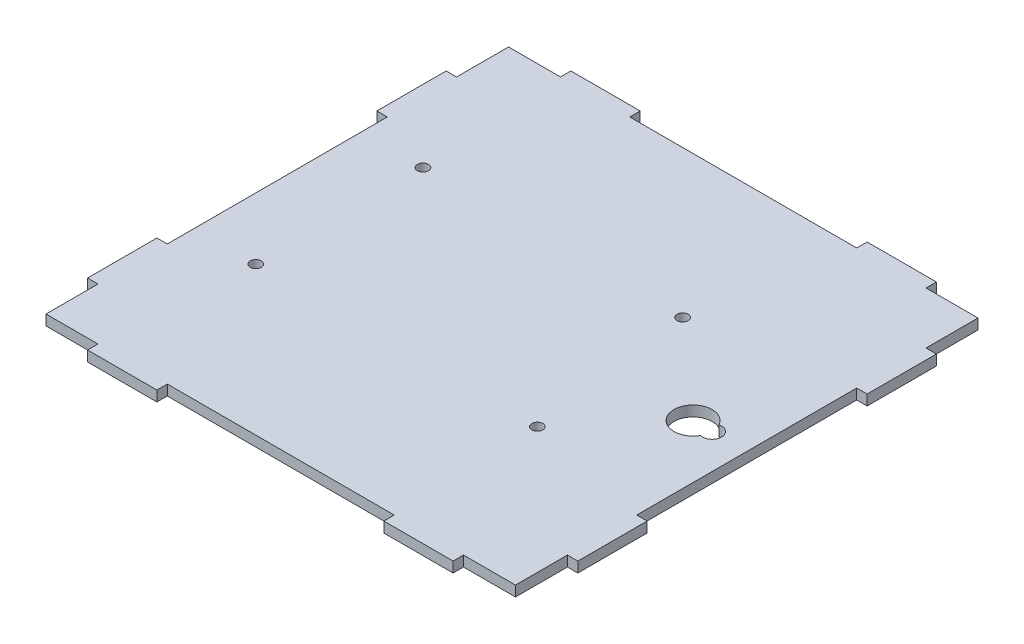
SolidWorks part; units mm, degrees
ref_plane "Спереди" through (0, 0, 0) normal (0, 0, 1) x (1, 0, 0)
ref_plane "Сверху" through (0, 0, 0) normal (0, 1, 0) x (1, 0, 0)
ref_plane "Справа" through (0, 0, 0) normal (1, 0, 0) x (0, 0, -1)
sketch "Sketch1" plane through (0, 0, 0) normal (0, 1, 0) x (1, 0, 0)
  line L0 (-47.661, 21.5312) -> (54.039, 21.5312) construction
  line L1 (-51.461, 61.5312) -> (84.039, 61.5312)
  line L2 (-51.461, 61.5312) -> (-51.461, -71.9688)
  line L3 (-51.461, -71.9688) -> (84.039, -71.9688)
  line L4 (84.039, 61.5312) -> (84.039, -71.9688)
  line L5 (54.039, -31.9688) -> (-47.661, -31.9688) construction
  line L6 (54.039, 21.5312) -> (54.039, -31.9688) construction
  point P0 (0, 0)
  point P8 (52.8389, -53.9712)
  point P9 (70.544, -51.7921)
  dimension "D1" = 40
  dimension "D2" = 40
  dimension "D3" = 30
extrude "Boss-Extrude1" add sketch "Sketch1" along normal blind 3
sketch "Sketch2" plane through (0, 3, 0) normal (0, 1, 0) x (1, 0, 0)
  line L0 (84.039, -71.9688) -> (84.039, 61.5312) construction
  line L1 (84.039, 46.5312) -> (87.039, 46.5312)
  line L2 (84.039, 46.5312) -> (84.039, 26.5312)
  line L3 (84.039, 26.5312) -> (87.039, 26.5312)
  line L4 (87.039, 46.5312) -> (87.039, 26.5312)
  line L5 (84.039, 61.5312) -> (-51.461, 61.5312) construction
  line L6 (84.039, -36.9688) -> (87.039, -36.9688)
  line L7 (84.039, -36.9688) -> (84.039, -56.9688)
  line L8 (84.039, -56.9688) -> (87.039, -56.9688)
  line L9 (87.039, -36.9688) -> (87.039, -56.9688)
  line L10 (69.039, 61.5312) -> (49.039, 61.5312)
  line L11 (69.039, 61.5312) -> (69.039, 64.5312)
  line L12 (69.039, 64.5312) -> (49.039, 64.5312)
  line L13 (49.039, 61.5312) -> (49.039, 64.5312)
  line L14 (-51.461, 61.5312) -> (-51.461, -71.9688) construction
  line L15 (-16.461, 61.5312) -> (-36.461, 61.5312)
  line L16 (-16.461, 61.5312) -> (-16.461, 64.5312)
  line L17 (-16.461, 64.5312) -> (-36.461, 64.5312)
  line L18 (-36.461, 61.5312) -> (-36.461, 64.5312)
  line L19 (-51.461, 46.5312) -> (-54.461, 46.5312)
  line L20 (-51.461, 46.5312) -> (-51.461, 26.5312)
  line L21 (-51.461, 26.5312) -> (-54.461, 26.5312)
  line L22 (-54.461, 46.5312) -> (-54.461, 26.5312)
  line L23 (-51.461, -71.9688) -> (84.039, -71.9688) construction
  line L24 (-51.461, -56.9688) -> (-54.461, -56.9688)
  line L25 (-51.461, -56.9688) -> (-51.461, -36.9688)
  line L26 (-51.461, -36.9688) -> (-54.461, -36.9688)
  line L27 (-54.461, -56.9688) -> (-54.461, -36.9688)
  line L28 (-36.461, -71.9688) -> (-16.461, -71.9688)
  line L29 (-36.461, -71.9688) -> (-36.461, -74.9688)
  line L30 (-36.461, -74.9688) -> (-16.461, -74.9688)
  line L31 (-16.461, -71.9688) -> (-16.461, -74.9688)
  line L33 (49.039, -71.9688) -> (69.039, -71.9688)
  line L34 (49.039, -71.9688) -> (49.039, -74.9688)
  line L35 (49.039, -74.9688) -> (69.039, -74.9688)
  line L36 (69.039, -71.9688) -> (69.039, -74.9688)
  dimension "D1" = 3
  dimension "D2" = 20
  dimension "D3" = 15
  dimension "D4" = 15
  dimension "D5" = 15
  dimension "D6" = 15
  dimension "D7" = 15
  dimension "D8" = 15
  dimension "D9" = 15
  dimension "D10" = 15
extrude "Boss-Extrude2" add sketch "Sketch2" against normal through all
sketch "Sketch3" plane through (0, 0, 0) normal (0, -1, 0) x (1, 0, 0)
  circle A0 centre (-33.661, 29.2287) radius 1.6
  circle A1 centre (47.619, 29.2287) radius 1.6
  circle A2 centre (41.269, -19.0313) radius 1.6
  circle A3 centre (-33.661, -19.0313) radius 1.6
  dimension "D1" = 3.2
extrude "Cut-Extrude1" cut sketch "Sketch3" against normal through all
sketch "Sketch4" plane through (0, 0, 0) normal (0, -1, 0) x (1, 0, 0)
  line L0 (84.039, 36.9688) -> (84.039, -26.5312) construction
  line L1 (84.039, 36.9688) -> (84.039, -26.5312) construction
  circle A0 centre (68.539, 5.2188) radius 5.5
  circle A1 centre (74.039, 5.2188) radius 2.75
  point P4 (84.039, 5.2188)
  dimension "D1" = 11
  dimension "D2" = 5.5
  dimension "D3" = 5.5
  dimension "D4" = 10
extrude "Cut-Extrude2" cut sketch "Sketch4" against normal through all contours A0 | A1
equation "\"D2@Sketch1\"=\"D1@Sketch1\""
equation "\"D4@Sketch2\"=\"D3@Sketch2\""
equation "\"D5@Sketch2\"=\"D3@Sketch2\""
equation "\"D6@Sketch2\"=\"D3@Sketch2\""
equation "\"D8@Sketch2\"=\"D3@Sketch2\""
equation "\"D9@Sketch2\"=\"D3@Sketch2\""
equation "\"D10@Sketch2\"=\"D3@Sketch2\""
equation "\"D7@Sketch2\"=\"D3@Sketch2\""
equation "\"D3@Sketch4\"=\"D2@Sketch4\""
